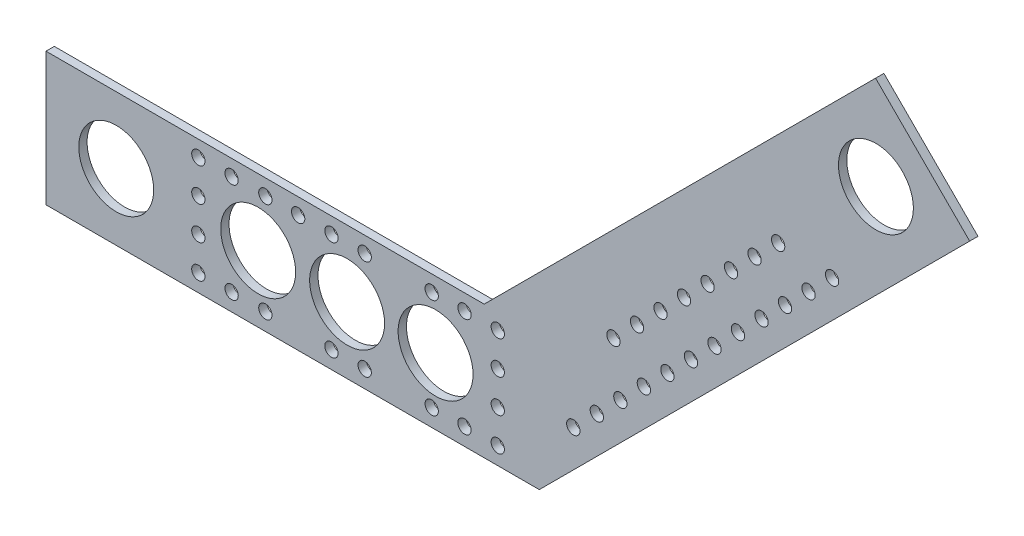
SolidWorks part; units mm, degrees
ref_plane "Front Plane" through (0, 0, 0) normal (0, 0, 1) x (1, 0, 0)
ref_plane "Top Plane" through (0, 0, 0) normal (0, 1, 0) x (1, 0, 0)
ref_plane "Right Plane" through (0, 0, 0) normal (1, 0, 0) x (0, 0, -1)
sketch "Sketch1" plane through (0, 0, 0) normal (0, 0, 1) x (1, 0, 0)
  line L0 (-59.6938, 4.2713) -> (-59.6938, -46.5287)
  line L1 (-59.6938, -46.5287) -> (128.6141, -46.5287)
  line L2 (128.6141, -46.5287) -> (292.9114, 117.7686)
  line L3 (292.9114, 117.7686) -> (256.9904, 153.6896)
  line L4 (256.9904, 153.6896) -> (107.5721, 4.2713)
  line L5 (107.5721, 4.2713) -> (-59.6938, 4.2713)
  circle A0 centre (141.5946, -19.421) radius 2.54
  circle A1 centre (150.5748, -10.4408) radius 2.54
  circle A2 centre (159.5551, -1.4605) radius 2.54
  circle A3 centre (168.5353, 7.5197) radius 2.54
  circle A4 centre (177.5156, 16.5) radius 2.54
  circle A5 centre (186.4958, 25.4803) radius 2.54
  circle A6 centre (195.4761, 34.4605) radius 2.54
  circle A7 centre (204.4564, 43.4408) radius 2.54
  circle A8 centre (213.4366, 52.421) radius 2.54
  circle A9 centre (222.4169, 61.4013) radius 2.54
  circle A10 centre (11.1589, -1.8121) radius 2.54 construction
  circle A11 centre (24.0402, -1.8121) radius 2.54 construction
  circle A12 centre (36.5589, -1.8121) radius 2.54 construction
  circle A13 centre (49.2589, -1.8121) radius 2.54 construction
  circle A14 centre (61.9589, -1.8121) radius 2.54 construction
  circle A15 centre (87.5402, -1.8121) radius 2.54 construction
  circle A16 centre (100.0589, -1.8121) radius 2.54 construction
  circle A17 centre (112.7589, -1.8121) radius 2.54 construction
  circle A18 centre (112.7589, -14.5121) radius 2.54 construction
  circle A19 centre (112.7589, -27.2121) radius 2.54 construction
  circle A20 centre (112.7589, -39.9121) radius 2.54 construction
  circle A21 centre (100.0589, -39.9121) radius 2.54 construction
  circle A22 centre (87.5402, -39.9121) radius 2.54 construction
  circle A23 centre (61.9589, -39.9121) radius 2.54 construction
  circle A24 centre (49.2589, -39.9121) radius 2.54 construction
  circle A25 centre (24.0402, -39.9121) radius 2.54 construction
  circle A26 centre (11.1589, -39.9121) radius 2.54 construction
  circle A27 centre (-1.5411, -39.9121) radius 2.54 construction
  circle A28 centre (-1.5411, -27.2121) radius 2.54 construction
  circle A29 centre (-1.5411, -14.5121) radius 2.54 construction
  circle A30 centre (-1.5411, -1.8121) radius 2.54 construction
  circle A31 centre (231.3971, 70.3815) radius 2.54
  circle A32 centre (240.3774, 79.3618) radius 2.54
  circle A36 centre (55.2538, -21.1287) radius 14.3002 construction
  circle A37 centre (-32.8842, -21.1287) radius 14.3002 construction
  circle A48 centre (11.1589, -1.8121) radius 2.54
  circle A49 centre (24.0402, -1.8121) radius 2.54
  circle A50 centre (36.5589, -1.8121) radius 2.54
  circle A51 centre (49.2589, -1.8121) radius 2.54
  circle A52 centre (61.9589, -1.8121) radius 2.54
  circle A53 centre (87.5402, -1.8121) radius 2.54
  circle A54 centre (100.0589, -1.8121) radius 2.54
  circle A55 centre (112.7589, -1.8121) radius 2.54
  circle A56 centre (112.7589, -14.5121) radius 2.54
  circle A57 centre (112.7589, -27.2121) radius 2.54
  circle A58 centre (112.7589, -39.9121) radius 2.54
  circle A59 centre (100.0589, -39.9121) radius 2.54
  circle A60 centre (87.5402, -39.9121) radius 2.54
  circle A61 centre (61.9589, -39.9121) radius 2.54
  circle A62 centre (49.2589, -39.9121) radius 2.54
  circle A63 centre (24.0402, -39.9121) radius 2.54
  circle A64 centre (11.1589, -39.9121) radius 2.54
  circle A65 centre (-1.5411, -39.9121) radius 2.54
  circle A66 centre (-1.5411, -27.2121) radius 2.54
  circle A67 centre (-1.5411, -14.5121) radius 2.54
  circle A68 centre (-1.5411, -1.8121) radius 2.54
  circle A74 centre (55.2538, -21.1287) radius 14.3002
  circle A75 centre (-32.8842, -21.1287) radius 14.3002
  circle A76 centre (257.1207, 117.8989) radius 14.3002
  circle A77 centre (21.3013, -21.1287) radius 14.3002
  circle A78 centre (89.024, -21.1287) radius 14.3002
  circle A79 centre (156.927, 17.7052) radius 2.54
  circle A80 centre (165.9073, 26.6854) radius 2.54
  circle A81 centre (174.8875, 35.6657) radius 2.54
  circle A82 centre (183.8678, 44.646) radius 2.54
  circle A83 centre (192.8481, 53.6262) radius 2.54
  circle A84 centre (201.8283, 62.6065) radius 2.54
  circle A85 centre (210.8086, 71.5867) radius 2.54
  circle A86 centre (219.7888, 80.567) radius 2.54
  point P70 (141.5946, -19.421)
  dimension "D4" = 245.11
  dimension "D6" = 33.7702
  dimension "D7" = 25.4
  dimension "D1" = 50.8
  dimension "D2" = 50.8
  dimension "D3" = 135
  dimension "D5" = 25.4
  dimension "D8" = 8
  dimension "D9" = 12
extrude "Boss-Extrude1" add sketch "Sketch1" along normal blind 3.175
